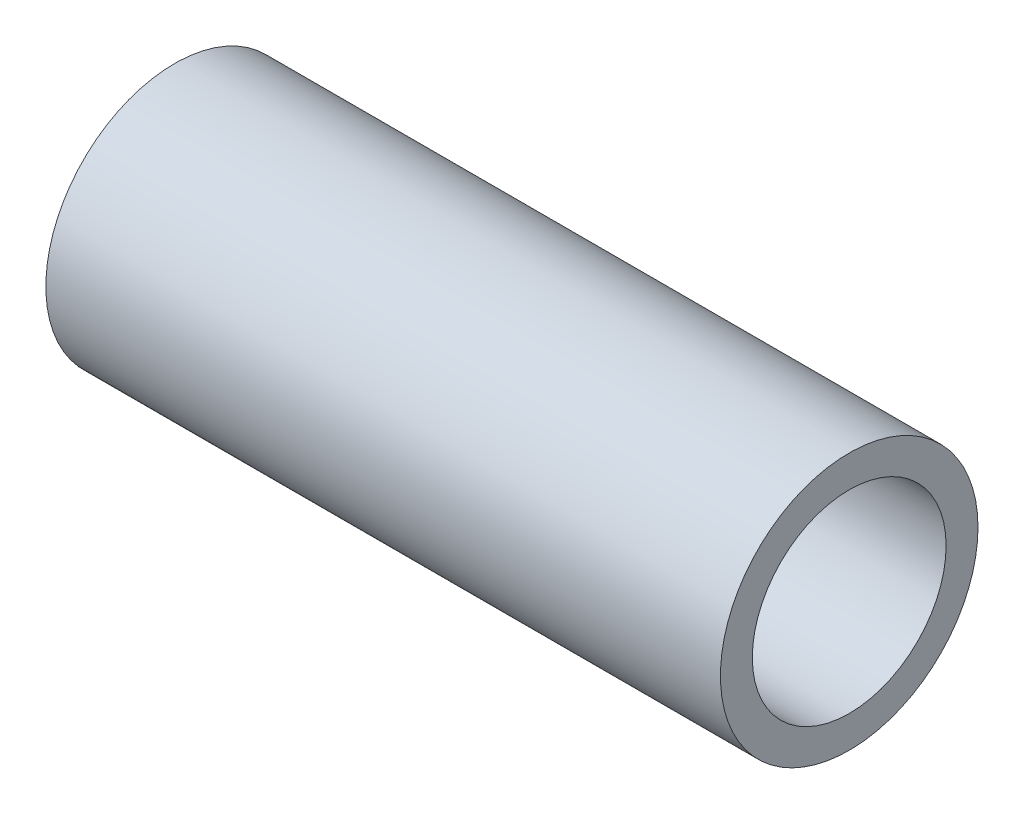
SolidWorks part; units mm, degrees
ref_plane "Front Plane" through (0, 0, 0) normal (0, 0, 1) x (1, 0, 0)
ref_plane "Top Plane" through (0, 0, 0) normal (0, 1, 0) x (1, 0, 0)
ref_plane "Right Plane" through (0, 0, 0) normal (1, 0, 0) x (0, 0, -1)
sketch "Sketch1" plane through (0, 0, 0) normal (1, 0, 0) x (0, 0, -1)
  circle A0 centre (0, 0) radius 10.5
  circle A1 centre (0, 0) radius 7.9
  dimension "D1" = 15.8
  dimension "D2" = 21
extrude "Boss-Extrude1" add sketch "Sketch1" along normal blind 55
